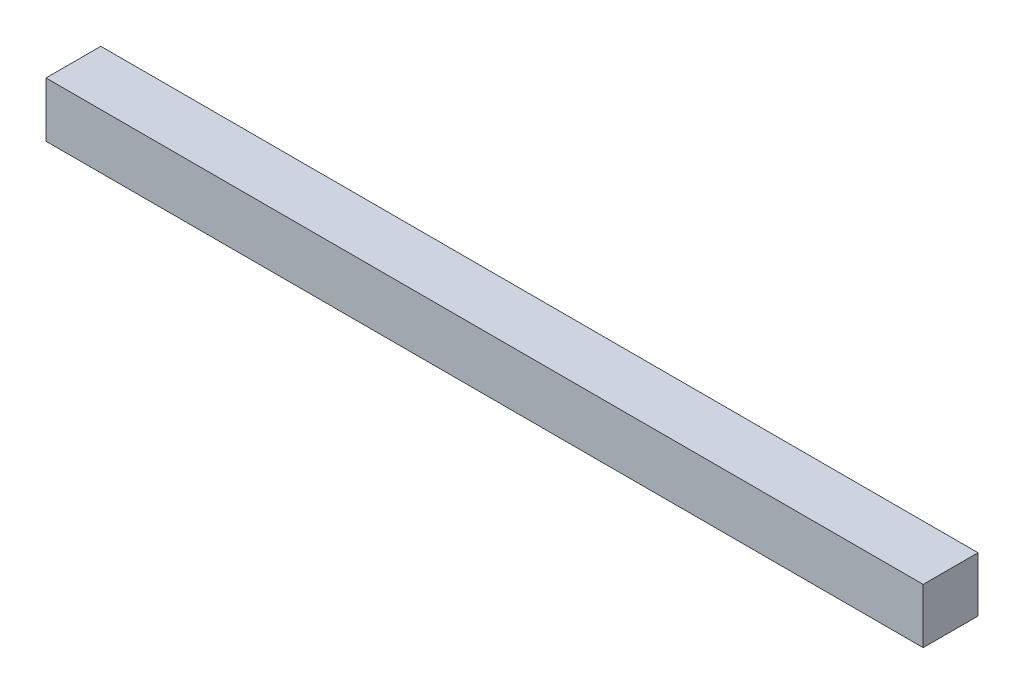
SolidWorks part; units mm, degrees
material "Brass"
ref_plane "Front Plane" through (0, 0, 0) normal (0, 0, 1) x (1, 0, 0)
ref_plane "Top Plane" through (0, 0, 0) normal (0, 1, 0) x (1, 0, 0)
ref_plane "Right Plane" through (0, 0, 0) normal (1, 0, 0) x (0, 0, -1)
sketch "Sketch1" plane through (0, 0, 0) normal (1, 0, 0) x (0, 0, -1)
  line L1 (3.175, -3.175) -> (-3.175, -3.175)
  line L2 (3.175, -3.175) -> (3.175, 3.175)
  line L3 (3.175, 3.175) -> (-3.175, 3.175)
  line L4 (-3.175, -3.175) -> (-3.175, 3.175)
  line L5 (3.175, -3.175) -> (-3.175, 3.175) construction
  line L6 (3.175, 3.175) -> (-3.175, -3.175) construction
  point P0 (0, 0)
  dimension "D1" = 6.35
  dimension "D2" = 6.35
extrude "Boss-Extrude1" add sketch "Sketch1" along normal mid plane 101.6
